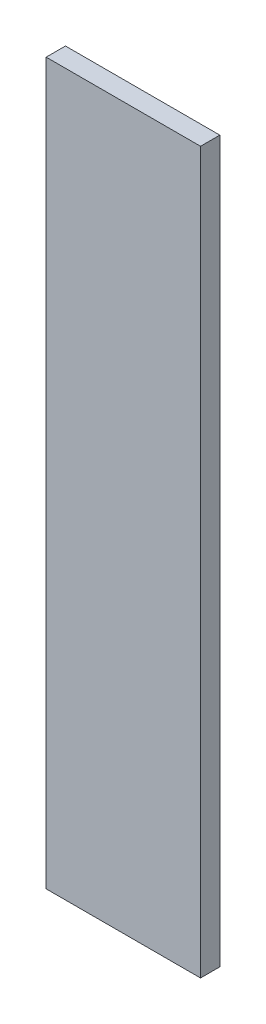
SolidWorks part; units mm, degrees
ref_plane "前视基准面" through (0, 0, 0) normal (0, 0, 1) x (1, 0, 0)
ref_plane "上视基准面" through (0, 0, 0) normal (0, 1, 0) x (1, 0, 0)
ref_plane "右视基准面" through (0, 0, 0) normal (1, 0, 0) x (0, 0, -1)
other "Configuration Table"
sketch "草图1" plane through (0, 0, 0) normal (0, 0, 1) x (1, 0, 0)
  line L0 (0, 0) -> (24, 0)
  line L1 (24, 0) -> (24, 112)
  line L2 (24, 112) -> (0, 112)
  line L3 (0, 112) -> (0, 0)
  dimension "width" = 24
  dimension "height" = 112
extrude "BlockExtrude" add sketch "草图1" along normal blind 3
